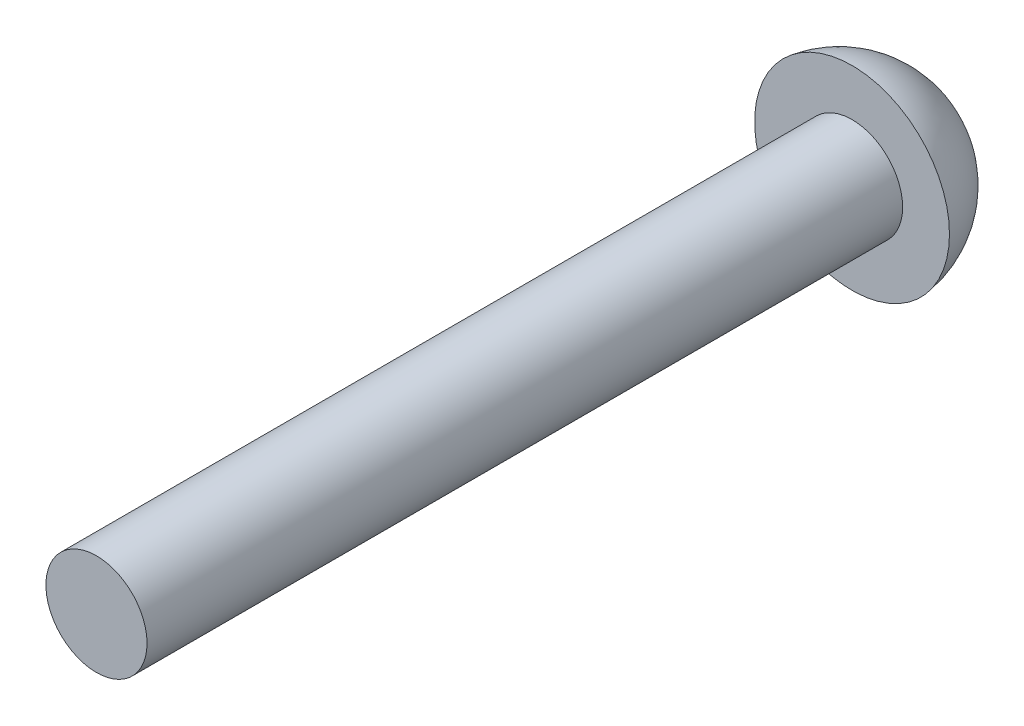
SolidWorks part; units mm, degrees
ref_plane "Front" through (0, 0, 0) normal (0, 0, 1) x (1, 0, 0)
ref_plane "Top" through (0, 0, 0) normal (0, 1, 0) x (1, 0, 0)
ref_plane "Right" through (0, 0, 0) normal (1, 0, 0) x (0, 0, -1)
sketch "Sketch1" plane through (0, 0, 0) normal (0, 1, 0) x (1, 0, 0)
  line L0 (0, 0) -> (0, 28.27)
  line L1 (0, 0) -> (1.7, 0)
  line L2 (1.7, 0) -> (1.7, 25.4)
  line L3 (1.7, 25.4) -> (3.275, 25.4)
  arc A0 (3.275, 25.4) -> (0, 28.27) centre (0, 24.9664) ccw
  dimension "D1" = 3.275
  dimension "D2" = 2.87
  dimension "D3" = 1.7
  dimension "D4" = 25.4
revolve "Revolve1" add sketch "Sketch1" angle 360 about L0
